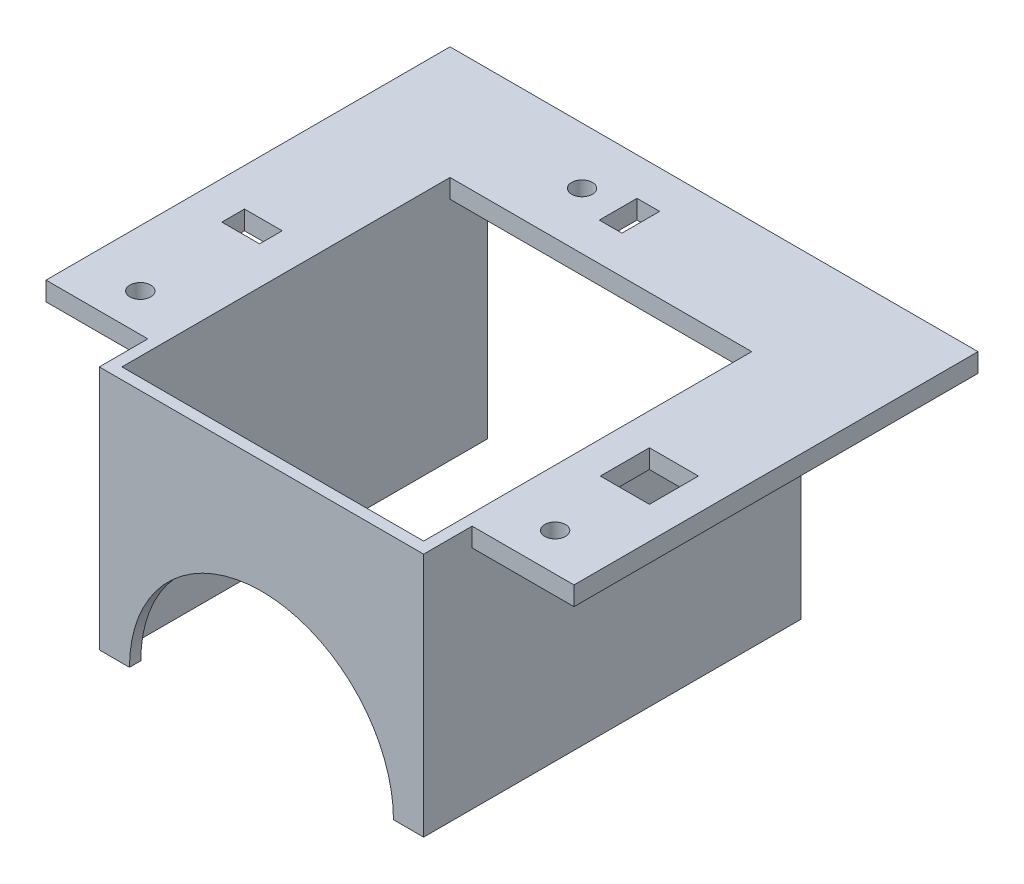
SolidWorks part; units mm, degrees
ref_plane "Front Plane" through (0, 0, 0) normal (0, 0, 1) x (1, 0, 0)
ref_plane "Top Plane" through (0, 0, 0) normal (0, 1, 0) x (1, 0, 0)
ref_plane "Right Plane" through (0, 0, 0) normal (1, 0, 0) x (0, 0, -1)
sketch "Sketch1" plane through (0, 0, 0) normal (0, 1, 0) x (1, 0, 0)
  line L0 (0, 0) -> (0, 100)
  line L1 (0, 100) -> (3, 100)
  line L2 (3, 100) -> (3, 3)
  line L3 (3, 3) -> (83, 3)
  line L4 (83, 3) -> (83, 100)
  line L5 (83, 100) -> (86, 100)
  line L6 (86, 100) -> (86, 0)
  line L7 (86, 0) -> (0, 0)
  dimension "D1" = 80
  dimension "D2" = 3
  dimension "D3" = 3
  dimension "D4" = 100
extrude "Boss-Extrude1" add sketch "Sketch1" along normal blind 60
sketch "Sketch2" plane through (0, 60, 0) normal (0, 1, 0) x (1, 0, 0)
  line L0 (0, 0) -> (86, 0) construction
  line L1 (83, 12.865) -> (113, 12.865)
  line L2 (83, 12.865) -> (83, 120)
  line L3 (83, 120) -> (113, 120)
  line L4 (113, 12.865) -> (113, 120)
  line L5 (3, 120) -> (-27, 120)
  line L6 (3, 120) -> (3, 12.865)
  line L7 (3, 12.865) -> (-27, 12.865)
  line L8 (-27, 120) -> (-27, 12.865)
  dimension "D1" = 30
  dimension "D2" = 12.865
  dimension "D3" = 12.865
  dimension "D4" = 107.135
  dimension "D5" = 107.135
extrude "Boss-Extrude2" add sketch "Sketch2" along normal blind 5
sketch "Sketch3" plane through (0, 65, 0) normal (0, 1, 0) x (1, 0, 0)
  line L1 (3, 120) -> (83, 120)
  line L2 (3, 120) -> (3, 90)
  line L3 (3, 90) -> (83, 90)
  line L4 (83, 120) -> (83, 90)
  dimension "D1" = 30
extrude "Boss-Extrude3" add sketch "Sketch3" against normal blind 5
sketch "Sketch5" plane through (0, 60, 0) normal (0, 1, 0) x (1, 0, 0)
  line L0 (0, 12.865) -> (0, 0)
  line L1 (0, 0) -> (86, 0)
  line L2 (86, 0) -> (86, 12.865)
  line L3 (86, 12.865) -> (83, 12.865)
  line L4 (83, 12.865) -> (83, 3)
  line L5 (83, 3) -> (3, 3)
  line L6 (83, 3) -> (3, 3) construction
  line L7 (3, 3) -> (3, 12.865)
  line L8 (3, 3) -> (3, 12.865) construction
  line L9 (0, 12.865) -> (3, 12.865) construction
  line L10 (0, 12.865) -> (3, 12.865)
extrude "Boss-Extrude4" add sketch "Sketch5" along normal blind 5
sketch "Sketch6" plane through (0, 0, 0) normal (0, 0, 1) x (1, 0, 0)
  line L1 (8, 0) -> (78, 0)
  line L2 (0, 0) -> (86, 0) construction
  arc A0 (8, 0) -> (78, 0) centre (43, 0) cw
  dimension "D1" = 35
extrude "Cut-Extrude2" cut sketch "Sketch6" against normal blind 5 contours A0 L1
sketch "Sketch7" plane through (0, 65, 0) normal (0, 1, 0) x (1, 0, 0)
  line L1 (3, 90) -> (83, 90) construction
  line L2 (-27, 12.865) -> (0, 12.865) construction
  line L3 (86, 12.865) -> (113, 12.865) construction
  line L4 (83, 90) -> (83, 3) construction
  line L5 (-27, 120) -> (-27, 12.865) construction
  circle A0 centre (-12, 22.865) radius 2.75
  circle A1 centre (23, 105) radius 2.75
  circle A2 centre (98, 22.865) radius 2.75
  dimension "D1" = 5.5
  dimension "D2" = 5.5
  dimension "D3" = 5.5
  dimension "D4" = 50
  dimension "D5" = 15
  dimension "D6" = 10
  dimension "D7" = 10
  dimension "D8" = 15
extrude "Cut-Extrude3" cut sketch "Sketch7" against normal through all
sketch "Sketch8" plane through (0, 65, 0) normal (0, 1, 0) x (1, 0, 0)
  line L1 (-1.25, 49.5) -> (-22.75, 49.5) construction
  line L2 (-17, 49.5) -> (-7, 49.5)
  line L3 (-17, 49.5) -> (-17, 55.5)
  line L4 (-17, 55.5) -> (-7, 55.5)
  line L5 (32.5811, 100) -> (38.5811, 100)
  line L6 (32.5811, 100) -> (32.5811, 110)
  line L7 (32.5811, 110) -> (38.5811, 110)
  line L8 (38.5811, 100) -> (38.5811, 110)
  line L10 (98, 22.865) -> (98, 120) construction
  line L11 (113, 120) -> (-27, 120) construction
  line L12 (68.7464, 105) -> (18.6962, 105) construction
  line L13 (-7, 49.5) -> (-7, 55.5)
  line L14 (-12, 120) -> (-12, 12.865) construction
  line L17 (-12, 55.5) -> (-12, 49.5) construction
  line L19 (113, 120) -> (-27, 120) construction
  line L20 (-27, 12.865) -> (0, 12.865) construction
  line L21 (3, 3) -> (3, 90) construction
  dimension "D1" = 10
  dimension "D2" = 6
  dimension "D3" = 10
  dimension "D4" = 6
  dimension "D5" = 15
  dimension "D6" = 5
  dimension "D7" = 5
extrude "Cut-Extrude4" cut sketch "Sketch8" against normal through all
ref_plane "Plane1" through (43, 0, 0) normal (-1, 0, 0) x (0, 0, 1)
sketch "Sketch9" plane through (0, 65, 0) normal (0, 1, 0) x (1, 0, 0)
  line L0 (3, 90) -> (3, 120) construction
  line L1 (113, 120) -> (-27, 120) construction
  line L2 (-12, 120) -> (-12, 12.865) construction
  line L3 (-27, 12.865) -> (0, 12.865) construction
  line L5 (3, 3) -> (3, 90) construction
  dimension "D1" = 15
sketch "Sketch10" plane through (0, 65, 0) normal (0, 1, 0) x (1, 0, 0)
  line L0 (91.5, 41.365) -> (104.5, 54.365) construction
  line L1 (91.5, 41.365) -> (104.5, 41.365)
  line L2 (91.5, 41.365) -> (91.5, 54.365)
  line L3 (91.5, 54.365) -> (104.5, 54.365)
  line L4 (104.5, 41.365) -> (104.5, 54.365)
  line L5 (91.5, 41.365) -> (104.5, 54.365) construction
  line L6 (91.5, 54.365) -> (104.5, 41.365) construction
  line L7 (91.5, 54.365) -> (104.5, 41.365) construction
  point P0 (98, 47.865)
  dimension "D1" = 13
extrude "Cut-Extrude5" cut sketch "Sketch10" against normal through all
